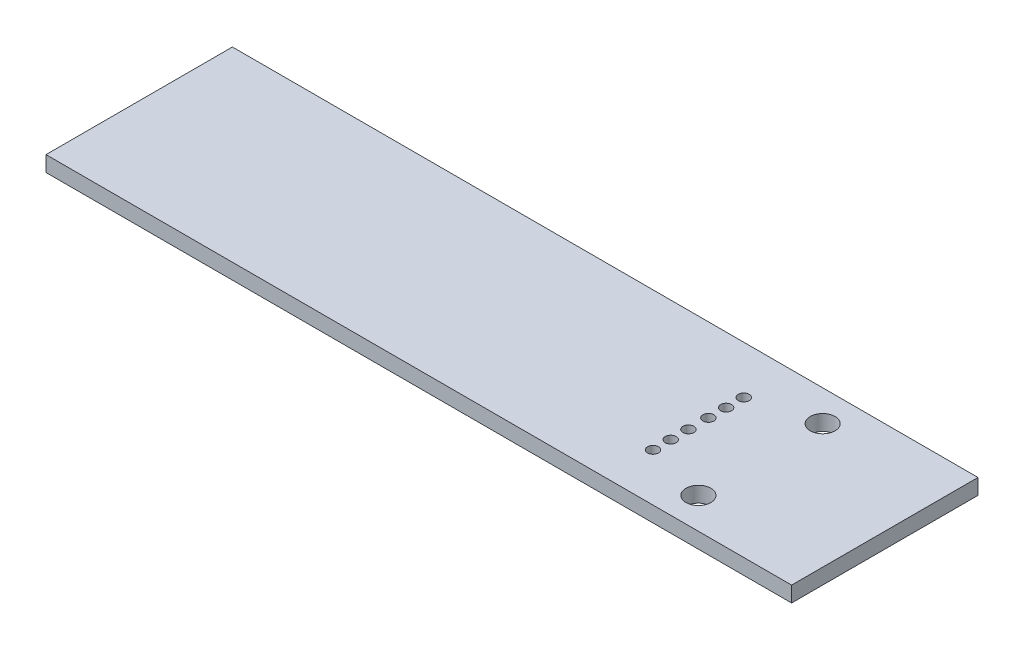
SolidWorks part; units mm, degrees
material "G-10 Garolite"
ref_plane "Front Plane" through (0, 0, 0) normal (0, 0, 1) x (1, 0, 0)
ref_plane "Top Plane" through (0, 0, 0) normal (0, 1, 0) x (1, 0, 0)
ref_plane "Right Plane" through (0, 0, 0) normal (1, 0, 0) x (0, 0, -1)
sketch "Sketch1" plane through (0, 0, 0) normal (0, 1, 0) x (1, 0, 0)
  line L0 (-38.1, 9.525) -> (38.1, 9.525)
  line L1 (-38.1, 9.525) -> (-38.1, -9.525)
  line L2 (38.1, 9.525) -> (38.1, -9.525)
  line L3 (-38.1, -9.525) -> (38.1, -9.525)
  line L4 (-38.1, 0) -> (38.1, 0) construction
  line L5 (25.4, 6.35) -> (25.4, -6.35) construction
  line L6 (19.05, 0) -> (19.05, 1.0216) construction
  line L7 (19.05, 1.0216) -> (19.05, 2.8292) construction
  line L8 (19.05, 2.8292) -> (19.05, 4.6369) construction
  line L9 (19.05, 0) -> (19.05, -1.0216) construction
  line L10 (19.05, -1.0216) -> (19.05, -2.8292) construction
  line L11 (19.05, -2.8292) -> (19.05, -4.6369) construction
  circle A0 centre (25.4, 6.35) radius 1.27
  circle A1 centre (25.4, -6.35) radius 1.27
  circle A2 centre (25.4, 6.35) radius 2.54 construction
  circle A3 centre (19.05, -4.6369) radius 0.5581
  circle A4 centre (19.05, -2.8292) radius 0.5581
  circle A5 centre (19.05, -1.0216) radius 0.5581
  circle A6 centre (19.05, 4.6369) radius 0.5581
  circle A7 centre (19.05, 2.8292) radius 0.5581
  circle A8 centre (19.05, 1.0216) radius 0.5581
  point P11 (25.4, 0)
  point P12 (27.94, 6.35)
  point P27 (15.2359, -1.0216)
  dimension "D4" = 2.54
  dimension "D5" = 5.08
  dimension "D1" = 19.05
  dimension "D2" = 76.2
  dimension "D3" = 12.7
  dimension "D6" = 12.7
  dimension "D7" = 10.16
  dimension "D8" = 19.05
extrude "Boss-Extrude1" add sketch "Sketch1" along normal blind 1.5875
